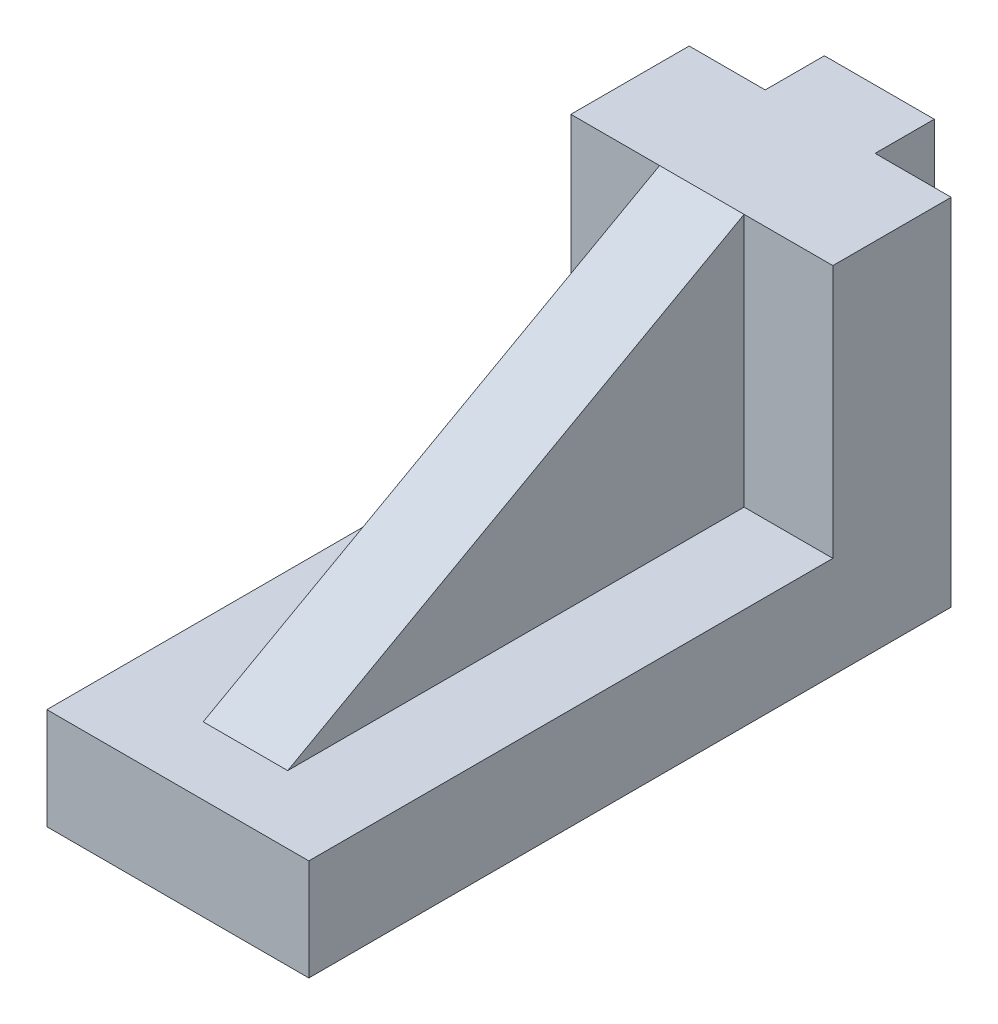
SolidWorks part; units mm, degrees
ref_plane "Alzado" through (0, 0, 0) normal (0, 0, 1) x (1, 0, 0)
ref_plane "Planta" through (0, 0, 0) normal (0, 1, 0) x (1, 0, 0)
ref_plane "Vista lateral" through (0, 0, 0) normal (1, 0, 0) x (0, 0, -1)
sketch "Croquis1" plane through (0, 0, 0) normal (1, 0, 0) x (0, 0, -1)
  line L1 (-14, 42) -> (0, 42)
  line L2 (-76, 12) -> (-76, 0)
  line L3 (-76, 0) -> (0, 0)
  line L4 (0, 42) -> (0, 0)
  line L7 (-76, 12) -> (-14, 12)
  line L8 (-14, 42) -> (-14, 12)
  point P0 (-44.2226, 48.2691)
  dimension "D1" = 76
  dimension "D2" = 42
  dimension "D3" = 14
  dimension "D4" = 12
extrude "Saliente-Extruir1" add sketch "Croquis1" along normal mid plane 31
sketch "Croquis2" plane through (0, 42, 0) normal (0, 1, 0) x (1, 0, 0)
  line L0 (15.5, 0) -> (-15.5, 0) construction
  line L1 (-6.5, 0) -> (6.5, 0)
  line L2 (-6.5, 0) -> (-6.5, 7)
  line L3 (-6.5, 7) -> (6.5, 7)
  line L4 (6.5, 0) -> (6.5, 7)
  line L5 (15.5, -14) -> (-15.5, -14) construction
  point P6 (0, 0)
  dimension "D1" = 13
  dimension "D2" = 21
extrude "Saliente-Extruir2" add sketch "Croquis2" against normal up to surface (42 mm away) up to face at (0, 0, 38)
sketch "Croquis3" plane through (0, 0, 0) normal (1, 0, 0) x (0, 0, -1)
  line L0 (-14, 42) -> (-68, 12)
  line L1 (-14, 12) -> (-76, 12) construction
  line L2 (-76, 12) -> (-76, 0) construction
  dimension "D1" = 8
rib "Nervio1" sketch "Croquis3" sketch "Croquis3" thickness 10 extrusion direction parallel to sketch draft on no parameters "D1"=10
